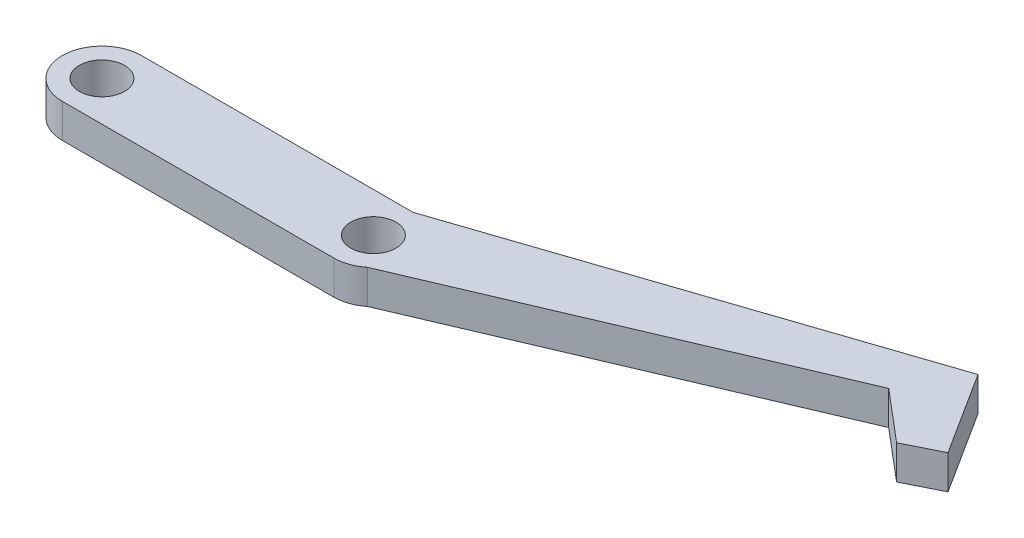
SolidWorks part; units mm, degrees
ref_plane "正面" through (0, 0, 0) normal (0, 0, 1) x (1, 0, 0)
ref_plane "平面" through (0, 0, 0) normal (0, 1, 0) x (1, 0, 0)
ref_plane "右側面" through (0, 0, 0) normal (1, 0, 0) x (0, 0, -1)
sketch "ｽｹｯﾁ1" plane through (0, 0, 0) normal (0, 1, 0) x (1, 0, 0)
  line L1 (-4.2202, -18.0078) -> (28.0917, -4.2378)
  line L3 (-6.4182, -11.784) -> (30.9755, 0.7725)
  line L4 (-30.4182, -18.784) -> (-6.4182, -18.784)
  line L5 (30.9755, 0.7725) -> (35.6362, -6.539)
  line L7 (-30.4182, -11.784) -> (-6.4182, -11.784)
  line L12 (35.6362, -6.539) -> (32.6067, -8.0537)
  line L13 (32.6067, -8.0537) -> (28.0917, -4.2378)
  circle A18 centre (-30.4182, -15.284) radius 2
  circle A19 centre (-6.4182, -15.284) radius 2
  circle A20 centre (-30.4182, -15.284) radius 3.5
  circle A21 centre (-6.4182, -15.284) radius 3.5
extrude "ﾎﾞｽ - 押し出し2" add sketch "ｽｹｯﾁ1" along normal blind 3 contours A21 L7 A20 L4 | A20 A18 | A21 A19 | A21 L1 L13 L12 L5 L3
